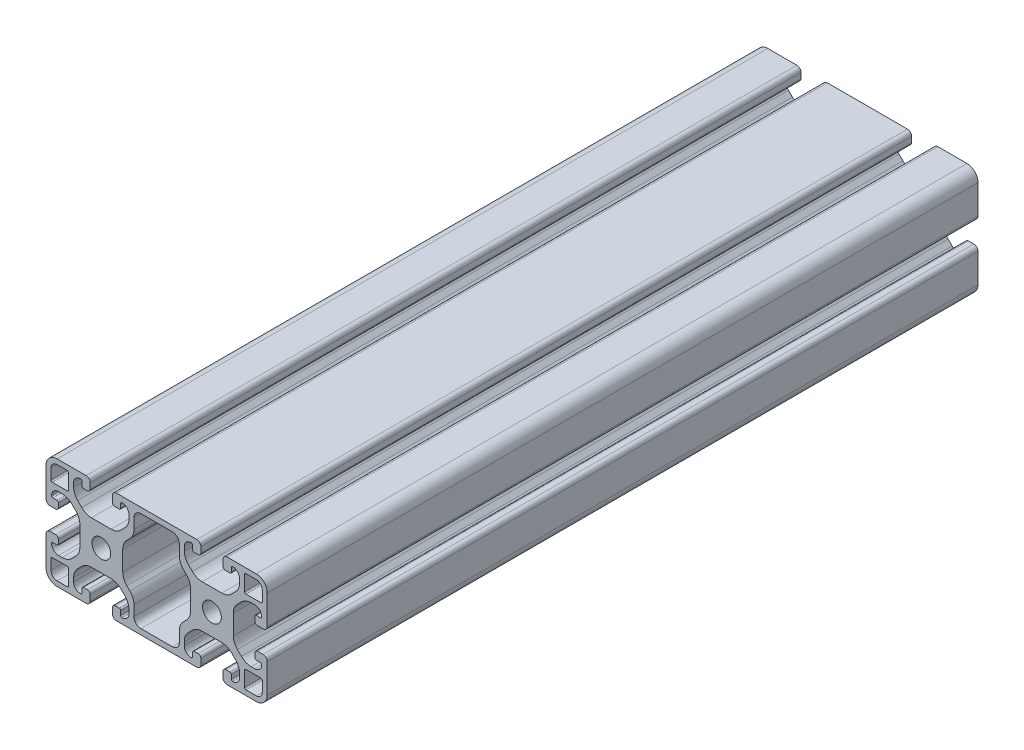
SolidWorks part; units mm, degrees
ref_plane "Plan de face" through (0, 0, 0) normal (0, 0, 1) x (1, 0, 0)
ref_plane "Plan de dessus" through (0, 0, 0) normal (0, 1, 0) x (1, 0, 0)
ref_plane "Plan de droite" through (0, 0, 0) normal (1, 0, 0) x (0, 0, -1)
ref_plane "Plan1" through (0, 0, 20) normal (0, 0, 1) x (1, 0, 0)
sketch "Esquisse1" plane through (0, 0, 20) normal (0, 0, 1) x (1, 0, 0)
  line L0 (66.5, 4.5) -> (65, 4.5)
  line L1 (64, 3.5) -> (64, 1.5)
  line L2 (65.5, 0) -> (76, 0)
  line L3 (80, 4) -> (80, 14.5)
  line L4 (78.5, 16) -> (76.5, 16)
  line L5 (75.5, 15) -> (75.5, 13.5)
  line L6 (76, 13) -> (77.5, 13)
  line L7 (75.5, 10) -> (74.1924, 10)
  line L8 (70.6569, 11.4645) -> (69.2145, 12.9069)
  line L9 (67.75, 16.4424) -> (67.75, 23.5576)
  line L10 (69.2145, 27.0931) -> (70.6569, 28.5355)
  line L11 (74.1924, 30) -> (75.5, 30)
  line L12 (77.5, 27) -> (76, 27)
  line L13 (75.5, 26.5) -> (75.5, 25)
  line L14 (76.5, 24) -> (78.5, 24)
  line L15 (80, 25.5) -> (80, 36)
  line L16 (76, 40) -> (65.5, 40)
  line L17 (64, 38.5) -> (64, 36.5)
  line L18 (65, 35.5) -> (66.5, 35.5)
  line L19 (67, 36) -> (67, 37.5)
  line L20 (70, 35.5) -> (70, 34.1924)
  line L21 (68.5355, 30.6569) -> (67.0931, 29.2145)
  line L22 (63.5576, 27.75) -> (56.4424, 27.75)
  line L23 (52.9069, 29.2145) -> (51.4645, 30.6569)
  line L24 (50, 34.1924) -> (50, 35.5)
  line L25 (53, 37.5) -> (53, 36)
  line L26 (53.5, 35.5) -> (55, 35.5)
  line L27 (56, 36.5) -> (56, 38.5)
  line L28 (54.5, 40) -> (25.5, 40)
  line L29 (24, 38.5) -> (24, 36.5)
  line L30 (25, 35.5) -> (26.5, 35.5)
  line L31 (27, 36) -> (27, 37.5)
  line L32 (30, 35.5) -> (30, 34.1924)
  line L33 (28.5355, 30.6569) -> (27.0931, 29.2145)
  line L34 (23.5576, 27.75) -> (16.4424, 27.75)
  line L35 (12.9069, 29.2145) -> (11.4645, 30.6569)
  line L36 (10, 34.1924) -> (10, 35.5)
  line L37 (13, 37.5) -> (13, 36)
  line L38 (13.5, 35.5) -> (15, 35.5)
  line L39 (16, 36.5) -> (16, 38.5)
  line L40 (14.5, 40) -> (4, 40)
  line L41 (0, 36) -> (0, 25.5)
  line L42 (1.5, 24) -> (3.5, 24)
  line L43 (4.5, 25) -> (4.5, 26.5)
  line L44 (4, 27) -> (2.5, 27)
  line L45 (4.5, 30) -> (5.8076, 30)
  line L46 (9.3431, 28.5355) -> (10.7855, 27.0931)
  line L47 (12.25, 23.5576) -> (12.25, 16.4424)
  line L48 (10.7855, 12.9069) -> (9.3431, 11.4645)
  line L49 (5.8076, 10) -> (4.5, 10)
  line L50 (2.5, 13) -> (4, 13)
  line L51 (4.5, 13.5) -> (4.5, 15)
  line L52 (3.5, 16) -> (1.5, 16)
  line L53 (0, 14.5) -> (0, 4)
  line L54 (4, 0) -> (14.5, 0)
  line L55 (16, 1.5) -> (16, 3.5)
  line L56 (15, 4.5) -> (13.5, 4.5)
  line L57 (13, 4) -> (13, 2.5)
  line L58 (10, 4.5) -> (10, 5.8076)
  line L59 (11.4645, 9.3431) -> (12.9069, 10.7855)
  line L60 (16.4424, 12.25) -> (23.5576, 12.25)
  line L61 (27.0931, 10.7855) -> (28.5355, 9.3431)
  line L62 (30, 5.8076) -> (30, 4.5)
  line L63 (27, 2.5) -> (27, 4)
  line L64 (26.5, 4.5) -> (25, 4.5)
  line L65 (24, 3.5) -> (24, 1.5)
  line L66 (25.5, 0) -> (54.5, 0)
  line L67 (56, 1.5) -> (56, 3.5)
  line L68 (55, 4.5) -> (53.5, 4.5)
  line L69 (53, 4) -> (53, 2.5)
  line L70 (50, 4.5) -> (50, 5.8076)
  line L71 (51.4645, 9.3431) -> (52.9069, 10.7855)
  line L72 (56.4424, 12.25) -> (63.5576, 12.25)
  line L73 (67.0931, 10.7855) -> (68.5355, 9.3431)
  line L74 (70, 5.8076) -> (70, 4.5)
  line L75 (67, 2.5) -> (67, 4)
  line L76 (31.8, 4.5) -> (31.8, 8.2503)
  line L77 (30.3355, 11.7858) -> (29.2145, 12.9069)
  line L78 (27.75, 16.4424) -> (27.75, 23.5576)
  line L79 (29.2145, 27.0931) -> (30.3355, 28.2142)
  line L80 (31.8, 31.7497) -> (31.8, 35.5)
  line L81 (34.3, 38) -> (45.7, 38)
  line L82 (48.2, 35.5) -> (48.2, 31.7497)
  line L83 (49.6645, 28.2142) -> (50.7855, 27.0931)
  line L84 (52.25, 23.5576) -> (52.25, 16.4424)
  line L85 (50.7855, 12.9069) -> (49.6645, 11.7858)
  line L86 (48.2, 8.2503) -> (48.2, 4.5)
  line L87 (45.7, 2) -> (34.3, 2)
  line L88 (7.7, 1.8) -> (4, 1.8)
  line L89 (1.8, 4) -> (1.8, 7.7)
  line L90 (2.3, 8.2) -> (7.7, 8.2)
  line L91 (8.2, 7.7) -> (8.2, 2.3)
  line L92 (72.3, 38.2) -> (76, 38.2)
  line L93 (78.2, 36) -> (78.2, 32.3)
  line L94 (77.7, 31.8) -> (72.3, 31.8)
  line L95 (71.8, 32.3) -> (71.8, 37.7)
  line L96 (78.2, 7.7) -> (78.2, 4)
  line L97 (76, 1.8) -> (72.3, 1.8)
  line L98 (71.8, 2.3) -> (71.8, 7.7)
  line L99 (72.3, 8.2) -> (77.7, 8.2)
  line L100 (1.8, 32.3) -> (1.8, 36)
  line L101 (4, 38.2) -> (7.7, 38.2)
  line L102 (8.2, 37.7) -> (8.2, 32.3)
  line L103 (7.7, 31.8) -> (2.3, 31.8)
  arc A0 (67, 4) -> (66.5, 4.5) centre (66.5, 4) ccw
  arc A1 (65, 4.5) -> (64, 3.5) centre (65, 3.5) ccw
  arc A2 (64, 1.5) -> (65.5, 0) centre (65.5, 1.5) ccw
  arc A3 (76, 0) -> (80, 4) centre (76, 4) ccw
  arc A4 (80, 14.5) -> (78.5, 16) centre (78.5, 14.5) ccw
  arc A5 (76.5, 16) -> (75.5, 15) centre (76.5, 15) ccw
  arc A6 (75.5, 13.5) -> (76, 13) centre (76, 13.5) ccw
  arc A7 (77.5, 13) -> (78, 12.5) centre (77.5, 12.5) cw
  arc A8 (78, 12.5) -> (75.5, 10) centre (75.5, 12.5) cw
  arc A9 (74.1924, 10) -> (70.6569, 11.4645) centre (74.1924, 15) cw
  arc A10 (69.2145, 12.9069) -> (67.75, 16.4424) centre (72.75, 16.4424) cw
  arc A11 (67.75, 23.5576) -> (69.2145, 27.0931) centre (72.75, 23.5576) cw
  arc A12 (70.6569, 28.5355) -> (74.1924, 30) centre (74.1924, 25) cw
  arc A13 (75.5, 30) -> (78, 27.5) centre (75.5, 27.5) cw
  arc A14 (78, 27.5) -> (77.5, 27) centre (77.5, 27.5) cw
  arc A15 (76, 27) -> (75.5, 26.5) centre (76, 26.5) ccw
  arc A16 (75.5, 25) -> (76.5, 24) centre (76.5, 25) ccw
  arc A17 (78.5, 24) -> (80, 25.5) centre (78.5, 25.5) ccw
  arc A18 (80, 36) -> (76, 40) centre (76, 36) ccw
  arc A19 (65.5, 40) -> (64, 38.5) centre (65.5, 38.5) ccw
  arc A20 (64, 36.5) -> (65, 35.5) centre (65, 36.5) ccw
  arc A21 (66.5, 35.5) -> (67, 36) centre (66.5, 36) ccw
  arc A22 (67, 37.5) -> (67.5, 38) centre (67.5, 37.5) cw
  arc A23 (67.5, 38) -> (70, 35.5) centre (67.5, 35.5) cw
  arc A24 (70, 34.1924) -> (68.5355, 30.6569) centre (65, 34.1924) cw
  arc A25 (67.0931, 29.2145) -> (63.5576, 27.75) centre (63.5576, 32.75) cw
  arc A26 (56.4424, 27.75) -> (52.9069, 29.2145) centre (56.4424, 32.75) cw
  arc A27 (51.4645, 30.6569) -> (50, 34.1924) centre (55, 34.1924) cw
  arc A28 (50, 35.5) -> (52.5, 38) centre (52.5, 35.5) cw
  arc A29 (52.5, 38) -> (53, 37.5) centre (52.5, 37.5) cw
  arc A30 (53, 36) -> (53.5, 35.5) centre (53.5, 36) ccw
  arc A31 (55, 35.5) -> (56, 36.5) centre (55, 36.5) ccw
  arc A32 (56, 38.5) -> (54.5, 40) centre (54.5, 38.5) ccw
  arc A33 (25.5, 40) -> (24, 38.5) centre (25.5, 38.5) ccw
  arc A34 (24, 36.5) -> (25, 35.5) centre (25, 36.5) ccw
  arc A35 (26.5, 35.5) -> (27, 36) centre (26.5, 36) ccw
  arc A36 (27, 37.5) -> (27.5, 38) centre (27.5, 37.5) cw
  arc A37 (27.5, 38) -> (30, 35.5) centre (27.5, 35.5) cw
  arc A38 (30, 34.1924) -> (28.5355, 30.6569) centre (25, 34.1924) cw
  arc A39 (27.0931, 29.2145) -> (23.5576, 27.75) centre (23.5576, 32.75) cw
  arc A40 (16.4424, 27.75) -> (12.9069, 29.2145) centre (16.4424, 32.75) cw
  arc A41 (11.4645, 30.6569) -> (10, 34.1924) centre (15, 34.1924) cw
  arc A42 (10, 35.5) -> (12.5, 38) centre (12.5, 35.5) cw
  arc A43 (12.5, 38) -> (13, 37.5) centre (12.5, 37.5) cw
  arc A44 (13, 36) -> (13.5, 35.5) centre (13.5, 36) ccw
  arc A45 (15, 35.5) -> (16, 36.5) centre (15, 36.5) ccw
  arc A46 (16, 38.5) -> (14.5, 40) centre (14.5, 38.5) ccw
  arc A47 (4, 40) -> (0, 36) centre (4, 36) ccw
  arc A48 (0, 25.5) -> (1.5, 24) centre (1.5, 25.5) ccw
  arc A49 (3.5, 24) -> (4.5, 25) centre (3.5, 25) ccw
  arc A50 (4.5, 26.5) -> (4, 27) centre (4, 26.5) ccw
  arc A51 (2.5, 27) -> (2, 27.5) centre (2.5, 27.5) cw
  arc A52 (2, 27.5) -> (4.5, 30) centre (4.5, 27.5) cw
  arc A53 (5.8076, 30) -> (9.3431, 28.5355) centre (5.8076, 25) cw
  arc A54 (10.7855, 27.0931) -> (12.25, 23.5576) centre (7.25, 23.5576) cw
  arc A55 (12.25, 16.4424) -> (10.7855, 12.9069) centre (7.25, 16.4424) cw
  arc A56 (9.3431, 11.4645) -> (5.8076, 10) centre (5.8076, 15) cw
  arc A57 (4.5, 10) -> (2, 12.5) centre (4.5, 12.5) cw
  arc A58 (2, 12.5) -> (2.5, 13) centre (2.5, 12.5) cw
  arc A59 (4, 13) -> (4.5, 13.5) centre (4, 13.5) ccw
  arc A60 (4.5, 15) -> (3.5, 16) centre (3.5, 15) ccw
  arc A61 (1.5, 16) -> (0, 14.5) centre (1.5, 14.5) ccw
  arc A62 (0, 4) -> (4, 0) centre (4, 4) ccw
  arc A63 (14.5, 0) -> (16, 1.5) centre (14.5, 1.5) ccw
  arc A64 (16, 3.5) -> (15, 4.5) centre (15, 3.5) ccw
  arc A65 (13.5, 4.5) -> (13, 4) centre (13.5, 4) ccw
  arc A66 (13, 2.5) -> (12.5, 2) centre (12.5, 2.5) cw
  arc A67 (12.5, 2) -> (10, 4.5) centre (12.5, 4.5) cw
  arc A68 (10, 5.8076) -> (11.4645, 9.3431) centre (15, 5.8076) cw
  arc A69 (12.9069, 10.7855) -> (16.4424, 12.25) centre (16.4424, 7.25) cw
  arc A70 (23.5576, 12.25) -> (27.0931, 10.7855) centre (23.5576, 7.25) cw
  arc A71 (28.5355, 9.3431) -> (30, 5.8076) centre (25, 5.8076) cw
  arc A72 (30, 4.5) -> (27.5, 2) centre (27.5, 4.5) cw
  arc A73 (27.5, 2) -> (27, 2.5) centre (27.5, 2.5) cw
  arc A74 (27, 4) -> (26.5, 4.5) centre (26.5, 4) ccw
  arc A75 (25, 4.5) -> (24, 3.5) centre (25, 3.5) ccw
  arc A76 (24, 1.5) -> (25.5, 0) centre (25.5, 1.5) ccw
  arc A77 (54.5, 0) -> (56, 1.5) centre (54.5, 1.5) ccw
  arc A78 (56, 3.5) -> (55, 4.5) centre (55, 3.5) ccw
  arc A79 (53.5, 4.5) -> (53, 4) centre (53.5, 4) ccw
  arc A80 (53, 2.5) -> (52.5, 2) centre (52.5, 2.5) cw
  arc A81 (52.5, 2) -> (50, 4.5) centre (52.5, 4.5) cw
  arc A82 (50, 5.8076) -> (51.4645, 9.3431) centre (55, 5.8076) cw
  arc A83 (52.9069, 10.7855) -> (56.4424, 12.25) centre (56.4424, 7.25) cw
  arc A84 (63.5576, 12.25) -> (67.0931, 10.7855) centre (63.5576, 7.25) cw
  arc A85 (68.5355, 9.3431) -> (70, 5.8076) centre (65, 5.8076) cw
  arc A86 (70, 4.5) -> (67.5, 2) centre (67.5, 4.5) cw
  arc A87 (67.5, 2) -> (67, 2.5) centre (67.5, 2.5) cw
  circle A88 centre (20, 20) radius 3.4
  circle A89 centre (60, 20) radius 3.4
  arc A90 (34.3, 2) -> (31.8, 4.5) centre (34.3, 4.5) cw
  arc A91 (31.8, 8.2503) -> (30.3355, 11.7858) centre (26.8, 8.2503) ccw
  arc A92 (29.2145, 12.9069) -> (27.75, 16.4424) centre (32.75, 16.4424) cw
  arc A93 (27.75, 23.5576) -> (29.2145, 27.0931) centre (32.75, 23.5576) cw
  arc A94 (30.3355, 28.2142) -> (31.8, 31.7497) centre (26.8, 31.7497) ccw
  arc A95 (31.8, 35.5) -> (34.3, 38) centre (34.3, 35.5) cw
  arc A96 (45.7, 38) -> (48.2, 35.5) centre (45.7, 35.5) cw
  arc A97 (48.2, 31.7497) -> (49.6645, 28.2142) centre (53.2, 31.7497) ccw
  arc A98 (50.7855, 27.0931) -> (52.25, 23.5576) centre (47.25, 23.5576) cw
  arc A99 (52.25, 16.4424) -> (50.7855, 12.9069) centre (47.25, 16.4424) cw
  arc A100 (49.6645, 11.7858) -> (48.2, 8.2503) centre (53.2, 8.2503) ccw
  arc A101 (48.2, 4.5) -> (45.7, 2) centre (45.7, 4.5) cw
  arc A102 (8.2, 2.3) -> (7.7, 1.8) centre (7.7, 2.3) cw
  arc A103 (4, 1.8) -> (1.8, 4) centre (4, 4) cw
  arc A104 (1.8, 7.7) -> (2.3, 8.2) centre (2.3, 7.7) cw
  arc A105 (7.7, 8.2) -> (8.2, 7.7) centre (7.7, 7.7) cw
  arc A106 (71.8, 37.7) -> (72.3, 38.2) centre (72.3, 37.7) cw
  arc A107 (76, 38.2) -> (78.2, 36) centre (76, 36) cw
  arc A108 (78.2, 32.3) -> (77.7, 31.8) centre (77.7, 32.3) cw
  arc A109 (72.3, 31.8) -> (71.8, 32.3) centre (72.3, 32.3) cw
  arc A110 (77.7, 8.2) -> (78.2, 7.7) centre (77.7, 7.7) cw
  arc A111 (78.2, 4) -> (76, 1.8) centre (76, 4) cw
  arc A112 (72.3, 1.8) -> (71.8, 2.3) centre (72.3, 2.3) cw
  arc A113 (71.8, 7.7) -> (72.3, 8.2) centre (72.3, 7.7) cw
  arc A114 (2.3, 31.8) -> (1.8, 32.3) centre (2.3, 32.3) cw
  arc A115 (1.8, 36) -> (4, 38.2) centre (4, 36) cw
  arc A116 (7.7, 38.2) -> (8.2, 37.7) centre (7.7, 37.7) cw
  arc A117 (8.2, 32.3) -> (7.7, 31.8) centre (7.7, 32.3) cw
extrude "Boss.-Extru.1" add sketch "Esquisse1" against normal blind 257
